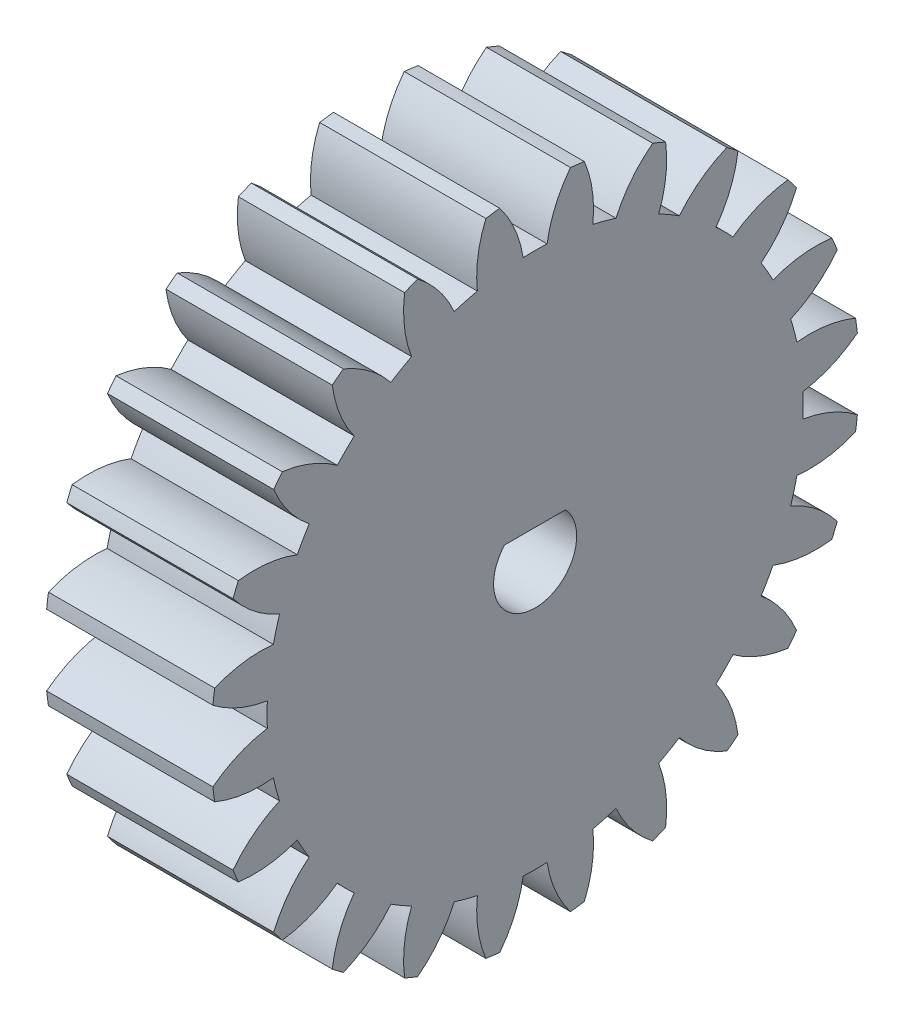
SolidWorks part; units mm, degrees
ref_plane "Plane1" through (0, 0, 0) normal (0, 0, 1) x (1, 0, 0)
ref_plane "Plane2" through (0, 0, 0) normal (0, 1, 0) x (1, 0, 0)
ref_plane "Plane3" through (0, 0, 0) normal (1, 0, 0) x (0, 0, -1)
sketch "HoldingSke" plane through (0, 0, 0) normal (0, 1, 0) x (1, 0, 0)
  line L0 (0, 0) -> (0.609, -0.2712)
  line L1 (-15, 0) -> (100, 0) construction
  line L2 (0, 0) -> (-2.1039, 2.3779)
  line L3 (0, 0) -> (-11.863, 4.5341)
  line L4 (0, 0) -> (7.8894, 3.5126)
  line L5 (0, 0) -> (-46.8476, -17.4728)
  line L6 (0, 0) -> (-8.2896, -5.593)
  line L7 (-2.1039, 2.3779) -> (8.6586, 51.2059)
  line L8 (-76.2, 54.61) -> (-75.3, 54.61)
  line L9 (-71.009, 38.7566) -> (-53.1078, 45.2721)
  line L10 (-76.2, 71.12) -> (104.1128, 71.12)
  line L11 (0, 0) -> (-10, 0)
  line L12 (-76.2, 101.6) -> (-76.147, 101.6)
  line L13 (24.9733, 27.94) -> (52.9518, 28.4284)
  line L14 (24.9733, 27.94) -> (24.9743, 27.94)
  line L15 (24.9733, 27.94) -> (100.4006, 29.5858)
  line L16 (-63.627, -1.5) -> (-12.827, -1.5)
  circle A0 centre (0, 0) radius 2.5
  circle A1 centre (0, 0) radius 16.124
  circle A2 centre (0, 0) radius 37.5
  circle A3 centre (0, 0) radius 2.5
  dimension "MHD" = 32.248
  dimension "Hub_dia" = 75
  dimension "Bore" = 5
  dimension "MBD" = 5
  dimension "Num_teeth" = 24
  dimension "Pitch" = 0.6667
  dimension "Overall_len" = 50
  dimension "Show_teeth" = 24
  dimension "Thickness" = 10
  dimension "OAL" = 50.0001
  dimension "T_dim" = 0.9
  dimension "Ap" = 20
  dimension "H" = 19.05
  dimension "Pitch_radius" = 180.3128
  dimension "Width" = 10
  dimension "Backlash" = 0.053
  dimension "Addendum_fac" = 1
  dimension "Dedendum_fac" = 1.25
  dimension "Clearance_fac" = 0.25
  dimension "Dedendum_add" = 0.001
  dimension "Module" = 1.5
sketch "BasProSke" plane through (0, 0, 0) normal (0, 1, 0) x (1, 0, 0)
  line L0 (-10, 0) -> (60, 0) construction
  line L1 (0, 0) -> (0, 19.5)
  line L2 (0, 0) -> (10, 0)
  line L3 (10, 0) -> (10, 19.5)
  line L4 (10, 19.5) -> (0, 19.5)
  dimension "Thickness" = 10
  dimension "Diameter" = 39
revolve "Base-Revolve" add sketch "BasProSke" angle 360 about L0
sketch "TooCutSke" plane through (0, 0, 0) normal (1, 0, 0) x (0, 0, -1)
  line L1 (0, 0) -> (0, 107) construction
  line L2 (0, 0) -> (-1.27, 17.9551) construction
  line L3 (0, 0) -> (-4.6904, 35.6272) construction
  line L4 (-1.27, 17.9551) -> (-2.3452, 17.8136) construction
  arc A0 (0.719, 16.108) -> (-0.719, 16.108) centre (0, 0) ccw
  arc A1 (2.1447, 19.4073) -> (-2.1447, 19.4073) centre (0, 0) ccw
  circle A2 centre (0, 0) radius 18 construction
  circle A3 centre (0, 0) radius 16.9145 construction
  arc A4 (-0.719, 16.108) -> (-2.1447, 19.4073) centre (-7.832, 14.992) ccw
  arc A5 (2.1447, 19.4073) -> (0.719, 16.108) centre (7.832, 14.992) ccw
  dimension "Root_dia" = 32.248
  dimension "Overcut_dia" = 39.0508
  dimension "Pitch_dia" = 36
  dimension "Base_dia" = 33.8289
  dimension "Flank_rad" = 7.2
  dimension "Half_ang" = 7.5
  dimension "Half_CT" = 1.0845
extrude "ToothCut" cut sketch "TooCutSke" along normal through all
fillet "Breaks" [suppressed] radius 0.03
fillet "RootFillets" [suppressed] radius 0.376
pattern_circular "TeethCuts" count 24 every 15 about axis through (-10, 0, 0) along (1, 0, 0) of "ToothCut", "RootFillets", "Breaks"
sketch "HubNeaOneSke" plane through (0, 0, 0) normal (-1, 0, 0) x (0, 0, 1)
  circle A0 centre (0, 0) radius 16.124
  dimension "Diameter" = 32.248
extrude "HubNearOne" [suppressed] add sketch "HubNeaOneSke" along normal blind 40.0001
sketch "HubNeaBotSke" plane through (0, 0, 0) normal (-1, 0, 0) x (0, 0, 1)
  circle A0 centre (0, 0) radius 16.124
  dimension "Diameter" = 32.248
extrude "HubNearBoth" [suppressed] add sketch "HubNeaBotSke" along normal blind 20
ref_plane "FarPln" through (10, 0, 0) normal (1, 0, 0) x (0, 0, -1)
sketch "HubFarSke" plane through (10, 0, 0) normal (1, 0, 0) x (0, 0, -1)
  circle A0 centre (0, 0) radius 16.124
  dimension "Diameter" = 32.248
extrude "HubFar" [suppressed] add sketch "HubFarSke" along normal blind 20
sketch "BorSke" plane through (0, 0, 0) normal (1, 0, 0) x (0, 0, -1)
  circle A0 centre (0, 0) radius 2.5
  dimension "Diameter" = 5
extrude "Bore" cut sketch "BorSke" along normal mid plane 100.0001
sketch "KeySke" plane through (0, 0, 0) normal (1, 0, 0) x (0, 0, -1)
  line L0 (-1, 0) -> (-1, 3.4)
  line L1 (-1, 3.4) -> (1, 3.4)
  line L2 (1, 3.4) -> (1, 0)
  line L3 (0, 0) -> (0, 34) construction
  line L4 (-1, 0) -> (1, 0)
  dimension "Offset" = 3.4
  dimension "Width" = 2
extrude "Keyway" [suppressed] cut sketch "KeySke" along normal mid plane 100.0001
pattern_circular "Keyway2" [suppressed] count 2 every 90 about axis through (-10, 0, 0) along (1, 0, 0)
sketch "Sketch1" plane through (10, 0, 0) normal (1, 0, 0) x (0, 0, -1)
  line L0 (1.833, 1.7) -> (-1.833, 1.7)
  circle A0 centre (0, 0) radius 2.5
  dimension "D2" = 5
  dimension "D1" = 1.7
extrude "Boss-Extrude1" add sketch "Sketch1" against normal blind 10 contours L0 A0
equation "' \"Module@HoldingSke\" = 6.35"
equation "' \"Num_teeth@HoldingSke\" = 12"
equation "' \"Ap@HoldingSke\" =  20"
equation "' \"Ap@HoldingSke\" = 20"
equation "' \"Width@HoldingSke\" = 0.5 * 25.4"
equation "' \"Hub_dia@HoldingSke\"= 1 * 25.4"
equation "' \"Hub_dia@HoldingSke\" = 1 * 25.4"
equation "' \"Overall_len@HoldingSke\" = 1.0 * 25.4"
equation "' \"Bore@HoldingSke\" = 0.75 * 25.4"
equation "' \"T_dim@HoldingSke\" = 0.1 * 25.4"
equation "' \"Width@KeySke\" = 0.25 * 25.4"
equation "' \"Show_teeth@HoldingSke\" = 13"
equation "' \"Backlash@HoldingSke\" = 0.009 * 25.4"
equation "' \"Addendum_fac@HoldingSke\" = 1.0"
equation "' \"Dedendum_fac@HoldingSke\" = 1.25"
equation "' \"Dedendum_add@HoldingSke\" = 0.00005 * 25.4"
equation "' \"Clearance_fac@HoldingSke\" = 0.25"
equation "\"Pitch@HoldingSke\" = 1 / \"Module@HoldingSke\""
equation "\"Overcut_dia@TooCutSke\" = (\"Num_teeth@HoldingSke\" + 2 * \"Addendum_fac@HoldingSke\") / \"Pitch@HoldingSke\" + 0.002 * 25.4"
equation "\"Pitch_dia@TooCutSke\" = \"Num_teeth@HoldingSke\" / \"Pitch@HoldingSke\""
equation "\"Base_dia@TooCutSke\" = \"Num_teeth@HoldingSke\" / \"Pitch@HoldingSke\" * cos((\"Ap@HoldingSke\"  * 3.14159265 / 180))"
equation "\"Root_dia@TooCutSke\" = (\"Num_teeth@HoldingSke\" + 2) / \"Pitch@HoldingSke\" - 2 * (\"Addendum_fac@HoldingSke\" + \"Dedendum_fac@HoldingSke\") / \"Pitch@HoldingSke\" - \"Dedendum_add@HoldingSke\" * 2"
equation "\"Half_ang@TooCutSke\" = 180 / \"Num_teeth@HoldingSke\""
equation "\"Half_CT@TooCutSke\" = \"Num_teeth@HoldingSke\" / \"Pitch@HoldingSke\" * sin((3.14159265 / 2 / \"Num_teeth@HoldingSke\")) / 2 - 7 * \"Backlash@HoldingSke\" / 4"
equation "\"Flank_rad@TooCutSke\" = \"Num_teeth@HoldingSke\" / \"Pitch@HoldingSke\" / 5"
equation "\"Radius@RootFillets\" = \"Clearance_fac@HoldingSke\" / \"Pitch@HoldingSke\" + \"Dedendum_add@HoldingSke\""
equation "\"Break_rad@Breaks\" = 0.02 / \"Pitch@HoldingSke\""
equation "\"Thickness@HoldingSke\" = \"Width@HoldingSke\""
equation "\"OAL@HoldingSke\" = \"Thickness@HoldingSke\""
equation "\"MHD@HoldingSke\" = (\"Num_teeth@HoldingSke\" + 2) / \"Pitch@HoldingSke\" - 2 * (\"Addendum_fac@HoldingSke\" + \"Dedendum_fac@HoldingSke\")  / \"Pitch@HoldingSke\" - \"Dedendum_add@HoldingSke\" * 2"
equation "\"MBD@HoldingSke\" = (\"Num_teeth@HoldingSke\" + 2) / \"Pitch@HoldingSke\" - 2 * (\"Addendum_fac@HoldingSke\" + \"Dedendum_fac@HoldingSke\")  / \"Pitch@HoldingSke\" - \"Dedendum_add@HoldingSke\" * 2 - 0.002 * 25.4"
equation "\"MHD@HoldingSke\" = ((sgn( \"MHD@HoldingSke\" - \"Hub_dia@HoldingSke\" )-1)*( \"MHD@HoldingSke\" - \"Hub_dia@HoldingSke\" ))/-2+ \"Hub_dia@HoldingSke\""
equation "\"MBD@HoldingSke\" = ((sgn( \"MBD@HoldingSke\" - \"Bore@HoldingSke\" )-1)*( \"MBD@HoldingSke\" - \"Bore@HoldingSke\" ))/-2+ \"Bore@HoldingSke\""
equation "\"OAL@HoldingSke\" = ((sgn( \"OAL@HoldingSke\" - \"Overall_len@HoldingSke\" )+1)*( \"OAL@HoldingSke\" - \"Overall_len@HoldingSke\" ))/2 + \"Overall_len@HoldingSke\" + 0.000002 * 25.4"
equation "\"Num_teeth@TeethCuts\" = int( \"Show_teeth@HoldingSke\" ) + 1"
equation "\"Num_teeth@TeethCuts\" = ((sgn( \"Num_teeth@TeethCuts\" - \"Num_teeth@HoldingSke\" )-1)*( \"Num_teeth@TeethCuts\" - \"Num_teeth@HoldingSke\" ))/-2+ \"Num_teeth@HoldingSke\""
equation "\"Num_teeth@TeethCuts\" = ((sgn( \"Num_teeth@TeethCuts\" - 2.0)+1)*( \"Num_teeth@TeethCuts\" - 2.0))/2 +2.0"
equation "\"Angle@TeethCuts\" = 360.0 / \"Num_teeth@HoldingSke\""
equation "\"Diameter@BasProSke\" = (\"Num_teeth@HoldingSke\" + 2 * \"Addendum_fac@HoldingSke\") / \"Pitch@HoldingSke\""
equation "\"Thickness@BasProSke\"  = \"Thickness@HoldingSke\""
equation "' \"Fillet_rad@BasProSke\" =  \"Thickness@HoldingSke\" * 0.05"
equation "' \"Fillet_rad@BasProSke\" = \"Thickness@HoldingSke\" * 0.05"
equation "\"MHD@HoldingSke\" = ((sgn( \"MHD@HoldingSke\" - \"Root_dia@TooCutSke\" )-1)*( \"MHD@HoldingSke\" - \"Root_dia@TooCutSke\" ))/-2+ \"Root_dia@TooCutSke\""
equation "\"Diameter@HubNeaOneSke\" = \"MHD@HoldingSke\""
equation "\"Length@HubNearOne\" = \"OAL@HoldingSke\" - \"Thickness@BasProSke\""
equation "\"Diameter@HubNeaBotSke\" = \"MHD@HoldingSke\""
equation "\"Length@HubNearBoth\" = ( \"OAL@HoldingSke\" - \"Thickness@BasProSke\" ) / 2.0"
equation "\"Thickness@FarPln\" = \"Thickness@BasProSke\""
equation "\"Diameter@HubFarSke\" = \"MHD@HoldingSke\""
equation "\"Length@HubFar\" = ( \"OAL@HoldingSke\" - \"Thickness@BasProSke\" ) / 2.0"
equation "\"Diameter@BorSke\" = \"MBD@HoldingSke\""
equation "\"D1@Bore\" = \"OAL@HoldingSke\" * 2.0"
equation "\"D1@Keyway\" = \"OAL@HoldingSke\" * 2.0"
equation "\"Offset@KeySke\" = \"T_dim@HoldingSke\" + \"MBD@HoldingSke\" / 2.0"
